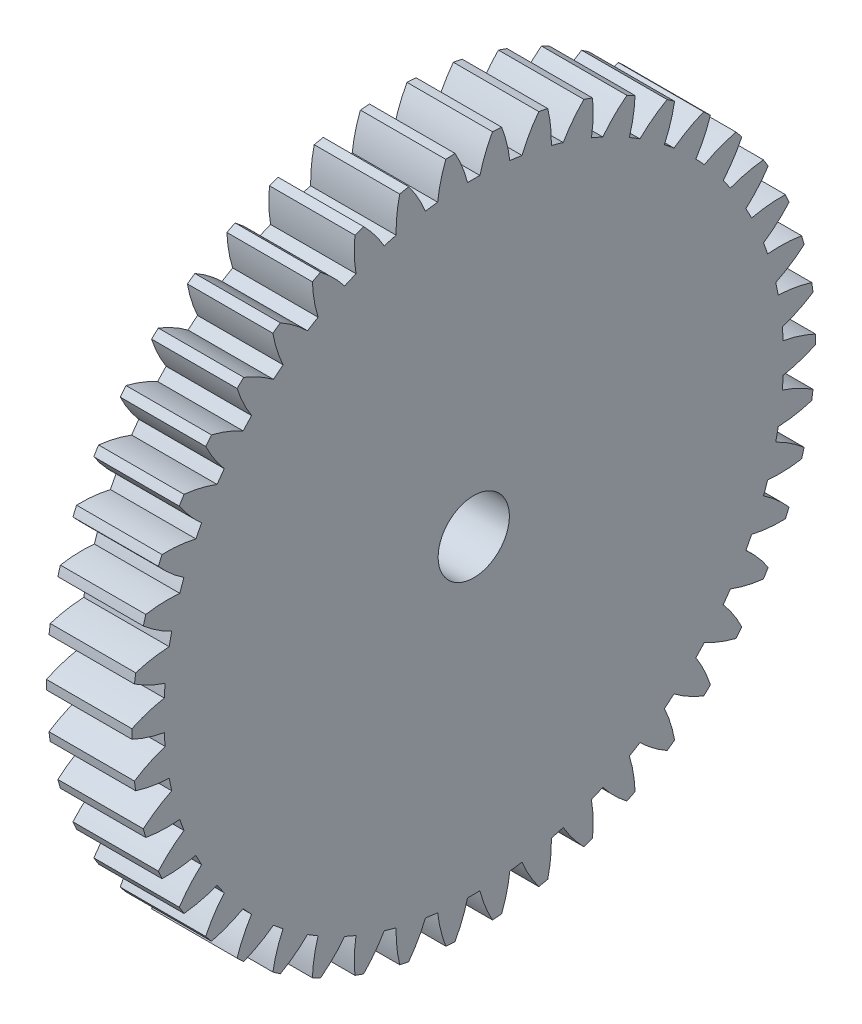
SolidWorks part; units mm, degrees
ref_plane "Plane1" through (0, 0, 0) normal (0, 0, 1) x (1, 0, 0)
ref_plane "Plane2" through (0, 0, 0) normal (0, 1, 0) x (1, 0, 0)
ref_plane "Plane3" through (0, 0, 0) normal (1, 0, 0) x (0, 0, -1)
sketch "HoldingSke" plane through (0, 0, 0) normal (0, 1, 0) x (1, 0, 0)
  line L0 (0, 0) -> (0.3473, -0.3597)
  line L1 (-15, 0) -> (100, 0) construction
  line L2 (0, 0) -> (-2.1039, 2.3779)
  line L3 (0, 0) -> (-11.863, 4.5341)
  line L4 (0, 0) -> (5.9991, 6.2122)
  line L5 (0, 0) -> (-46.8476, -17.4728)
  line L6 (0, 0) -> (-9.9476, -6.7116)
  line L7 (-2.1039, 2.3779) -> (8.6586, 51.2059)
  line L8 (-76.2, 54.61) -> (-74.4, 54.61)
  line L9 (-71.009, 38.7566) -> (-53.1078, 45.2721)
  line L10 (-76.2, 71.12) -> (104.1128, 71.12)
  line L11 (0, 0) -> (-12, 0)
  line L12 (-76.2, 101.6) -> (-76.133, 101.6)
  line L13 (24.9733, 27.94) -> (52.9518, 28.4284)
  line L14 (24.9733, 27.94) -> (24.9743, 27.94)
  line L15 (24.9733, 27.94) -> (100.4006, 29.5858)
  line L16 (-63.627, -2) -> (-12.827, -2)
  circle A0 centre (0, 0) radius 5
  circle A1 centre (0, 0) radius 37.5
  circle A2 centre (0, 0) radius 37.5
  circle A3 centre (0, 0) radius 5
  dimension "MHD" = 75
  dimension "Hub_dia" = 75
  dimension "Overall_len" = 50
  dimension "OAL" = 50.0001
  dimension "Ap" = 20
  dimension "H" = 19.05
  dimension "Pitch_radius" = 180.3128
  dimension "Addendum_fac" = 1
  dimension "Dedendum_fac" = 1.25
  dimension "Clearance_fac" = 0.25
  dimension "Dedendum_add" = 0.001
sketch "BasProSke" plane through (0, 0, 0) normal (0, 1, 0) x (1, 0, 0)
  line L0 (-10, 0) -> (60, 0) construction
  line L1 (0, 0) -> (0, 48)
  line L2 (0, 0) -> (12, 0)
  line L3 (12, 0) -> (12, 48)
  line L4 (12, 48) -> (0, 48)
revolve "Base-Revolve" add sketch "BasProSke" angle 360 about L0
sketch "TooCutSke" plane through (0, 0, 0) normal (1, 0, 0) x (0, 0, -1)
  line L1 (0, 0) -> (0, 107) construction
  line L2 (0, 0) -> (-1.6877, 45.969) construction
  line L3 (0, 0) -> (-6.2752, 91.7397) construction
  line L4 (-1.6877, 45.969) -> (-3.1376, 45.8699) construction
  arc A0 (0.8684, 43.4903) -> (-0.8684, 43.4903) centre (0, 0) ccw
  arc A1 (2.6462, 47.9524) -> (-2.6462, 47.9524) centre (0, 0) ccw
  circle A2 centre (0, 0) radius 46 construction
  circle A3 centre (0, 0) radius 43.2259 construction
  arc A4 (-0.8684, 43.4903) -> (-2.6462, 47.9524) centre (-18.7044, 38.9695) ccw
  arc A5 (2.6462, 47.9524) -> (0.8684, 43.4903) centre (18.7044, 38.9695) ccw
  dimension "Half_ang" = 3.913
extrude "ToothCut" cut sketch "TooCutSke" along normal through all
fillet "Breaks" [suppressed] radius 0.04
fillet "RootFillets" [suppressed] radius 0.501
pattern_circular "TeethCuts" count 46 every 7.826 about axis through (-10, 0, 0) along (1, 0, 0) of "ToothCut", "RootFillets", "Breaks"
sketch "HubNeaOneSke" plane through (0, 0, 0) normal (-1, 0, 0) x (0, 0, 1)
  circle A0 centre (0, 0) radius 37.5
  dimension "Diameter" = 75
extrude "HubNearOne" [suppressed] add sketch "HubNeaOneSke" along normal blind 38.0001
sketch "HubNeaBotSke" plane through (0, 0, 0) normal (-1, 0, 0) x (0, 0, 1)
  circle A0 centre (0, 0) radius 37.5
  dimension "Diameter" = 75
extrude "HubNearBoth" [suppressed] add sketch "HubNeaBotSke" along normal blind 19
ref_plane "FarPln" through (12, 0, 0) normal (1, 0, 0) x (0, 0, -1)
sketch "HubFarSke" plane through (12, 0, 0) normal (1, 0, 0) x (0, 0, -1)
  circle A0 centre (0, 0) radius 37.5
  dimension "Diameter" = 75
extrude "HubFar" [suppressed] add sketch "HubFarSke" along normal blind 19
sketch "BorSke" plane through (0, 0, 0) normal (1, 0, 0) x (0, 0, -1)
  circle A0 centre (0, 0) radius 5
extrude "Bore" cut sketch "BorSke" along normal mid plane 100.0001
sketch "KeySke" plane through (0, 0, 0) normal (1, 0, 0) x (0, 0, -1)
  line L0 (-2, 0) -> (-2, 6.8)
  line L1 (-2, 6.8) -> (2, 6.8)
  line L2 (2, 6.8) -> (2, 0)
  line L3 (0, 0) -> (0, 34) construction
  line L4 (-2, 0) -> (2, 0)
  dimension "Width" = 12
extrude "Keyway" [suppressed] cut sketch "KeySke" along normal mid plane 100.0001
pattern_circular "Keyway2" [suppressed] count 2 every 90 about axis through (-10, 0, 0) along (1, 0, 0)
equation "' \"Module@HoldingSke\" = 6.35"
equation "' \"Num_teeth@HoldingSke\" = 12"
equation "' \"Ap@HoldingSke\" =  20"
equation "' \"Ap@HoldingSke\" = 20"
equation "' \"Width@HoldingSke\" = 0.5 * 25.4"
equation "' \"Hub_dia@HoldingSke\"= 1 * 25.4"
equation "' \"Hub_dia@HoldingSke\" = 1 * 25.4"
equation "' \"Overall_len@HoldingSke\" = 1.0 * 25.4"
equation "' \"Bore@HoldingSke\" = 0.75 * 25.4"
equation "' \"T_dim@HoldingSke\" = 0.1 * 25.4"
equation "' \"Width@KeySke\" = 0.25 * 25.4"
equation "' \"Show_teeth@HoldingSke\" = 13"
equation "' \"Backlash@HoldingSke\" = 0.009 * 25.4"
equation "' \"Addendum_fac@HoldingSke\" = 1.0"
equation "' \"Dedendum_fac@HoldingSke\" = 1.25"
equation "' \"Dedendum_add@HoldingSke\" = 0.00005 * 25.4"
equation "' \"Clearance_fac@HoldingSke\" = 0.25"
equation "\"Pitch@HoldingSke\" = 1 / \"Module@HoldingSke\""
equation "\"Overcut_dia@TooCutSke\" = (\"Num_teeth@HoldingSke\" + 2 * \"Addendum_fac@HoldingSke\") / \"Pitch@HoldingSke\" + 0.002 * 25.4"
equation "\"Pitch_dia@TooCutSke\" = \"Num_teeth@HoldingSke\" / \"Pitch@HoldingSke\""
equation "\"Base_dia@TooCutSke\" = \"Num_teeth@HoldingSke\" / \"Pitch@HoldingSke\" * cos((\"Ap@HoldingSke\"  * 3.14159265 / 180))"
equation "\"Root_dia@TooCutSke\" = (\"Num_teeth@HoldingSke\" + 2) / \"Pitch@HoldingSke\" - 2 * (\"Addendum_fac@HoldingSke\" + \"Dedendum_fac@HoldingSke\") / \"Pitch@HoldingSke\" - \"Dedendum_add@HoldingSke\" * 2"
equation "\"Half_ang@TooCutSke\" = 180 / \"Num_teeth@HoldingSke\""
equation "\"Half_CT@TooCutSke\" = \"Num_teeth@HoldingSke\" / \"Pitch@HoldingSke\" * sin((3.14159265 / 2 / \"Num_teeth@HoldingSke\")) / 2 - 7 * \"Backlash@HoldingSke\" / 4"
equation "\"Flank_rad@TooCutSke\" = \"Num_teeth@HoldingSke\" / \"Pitch@HoldingSke\" / 5"
equation "\"Radius@RootFillets\" = \"Clearance_fac@HoldingSke\" / \"Pitch@HoldingSke\" + \"Dedendum_add@HoldingSke\""
equation "\"Break_rad@Breaks\" = 0.02 / \"Pitch@HoldingSke\""
equation "\"Thickness@HoldingSke\" = \"Width@HoldingSke\""
equation "\"OAL@HoldingSke\" = \"Thickness@HoldingSke\""
equation "\"MHD@HoldingSke\" = (\"Num_teeth@HoldingSke\" + 2) / \"Pitch@HoldingSke\" - 2 * (\"Addendum_fac@HoldingSke\" + \"Dedendum_fac@HoldingSke\")  / \"Pitch@HoldingSke\" - \"Dedendum_add@HoldingSke\" * 2"
equation "\"MBD@HoldingSke\" = (\"Num_teeth@HoldingSke\" + 2) / \"Pitch@HoldingSke\" - 2 * (\"Addendum_fac@HoldingSke\" + \"Dedendum_fac@HoldingSke\")  / \"Pitch@HoldingSke\" - \"Dedendum_add@HoldingSke\" * 2 - 0.002 * 25.4"
equation "\"MHD@HoldingSke\" = ((sgn( \"MHD@HoldingSke\" - \"Hub_dia@HoldingSke\" )-1)*( \"MHD@HoldingSke\" - \"Hub_dia@HoldingSke\" ))/-2+ \"Hub_dia@HoldingSke\""
equation "\"MBD@HoldingSke\" = ((sgn( \"MBD@HoldingSke\" - \"Bore@HoldingSke\" )-1)*( \"MBD@HoldingSke\" - \"Bore@HoldingSke\" ))/-2+ \"Bore@HoldingSke\""
equation "\"OAL@HoldingSke\" = ((sgn( \"OAL@HoldingSke\" - \"Overall_len@HoldingSke\" )+1)*( \"OAL@HoldingSke\" - \"Overall_len@HoldingSke\" ))/2 + \"Overall_len@HoldingSke\" + 0.000002 * 25.4"
equation "\"Num_teeth@TeethCuts\" = int( \"Show_teeth@HoldingSke\" ) + 1"
equation "\"Num_teeth@TeethCuts\" = ((sgn( \"Num_teeth@TeethCuts\" - \"Num_teeth@HoldingSke\" )-1)*( \"Num_teeth@TeethCuts\" - \"Num_teeth@HoldingSke\" ))/-2+ \"Num_teeth@HoldingSke\""
equation "\"Num_teeth@TeethCuts\" = ((sgn( \"Num_teeth@TeethCuts\" - 2.0)+1)*( \"Num_teeth@TeethCuts\" - 2.0))/2 +2.0"
equation "\"Angle@TeethCuts\" = 360.0 / \"Num_teeth@HoldingSke\""
equation "\"Diameter@BasProSke\" = (\"Num_teeth@HoldingSke\" + 2 * \"Addendum_fac@HoldingSke\") / \"Pitch@HoldingSke\""
equation "\"Thickness@BasProSke\"  = \"Thickness@HoldingSke\""
equation "' \"Fillet_rad@BasProSke\" =  \"Thickness@HoldingSke\" * 0.05"
equation "' \"Fillet_rad@BasProSke\" = \"Thickness@HoldingSke\" * 0.05"
equation "\"MHD@HoldingSke\" = ((sgn( \"MHD@HoldingSke\" - \"Root_dia@TooCutSke\" )-1)*( \"MHD@HoldingSke\" - \"Root_dia@TooCutSke\" ))/-2+ \"Root_dia@TooCutSke\""
equation "\"Diameter@HubNeaOneSke\" = \"MHD@HoldingSke\""
equation "\"Length@HubNearOne\" = \"OAL@HoldingSke\" - \"Thickness@BasProSke\""
equation "\"Diameter@HubNeaBotSke\" = \"MHD@HoldingSke\""
equation "\"Length@HubNearBoth\" = ( \"OAL@HoldingSke\" - \"Thickness@BasProSke\" ) / 2.0"
equation "\"Thickness@FarPln\" = \"Thickness@BasProSke\""
equation "\"Diameter@HubFarSke\" = \"MHD@HoldingSke\""
equation "\"Length@HubFar\" = ( \"OAL@HoldingSke\" - \"Thickness@BasProSke\" ) / 2.0"
equation "\"Diameter@BorSke\" = \"MBD@HoldingSke\""
equation "\"D1@Bore\" = \"OAL@HoldingSke\" * 2.0"
equation "\"D1@Keyway\" = \"OAL@HoldingSke\" * 2.0"
equation "\"Offset@KeySke\" = \"T_dim@HoldingSke\" + \"MBD@HoldingSke\" / 2.0"
